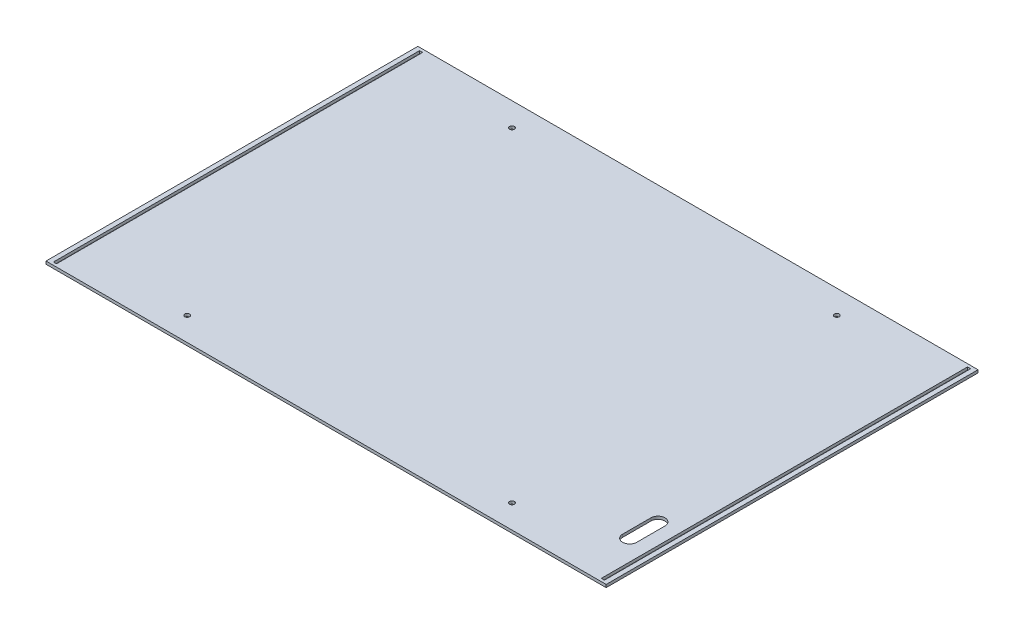
SolidWorks part; units mm, degrees
ref_plane "Front Plane" through (0, 0, 0) normal (0, 0, 1) x (1, 0, 0)
ref_plane "Top Plane" through (0, 0, 0) normal (0, 1, 0) x (1, 0, 0)
ref_plane "Right Plane" through (0, 0, 0) normal (1, 0, 0) x (0, 0, -1)
sketch "Sketch1" plane through (0, 0, 0) normal (0, 1, 0) x (1, 0, 0)
  line L1 (-297.5, 197.5) -> (297.5, 197.5)
  line L2 (-297.5, 197.5) -> (-297.5, -197.5)
  line L3 (-297.5, -197.5) -> (297.5, -197.5)
  line L4 (297.5, 197.5) -> (297.5, -197.5)
  line L5 (-297.5, 197.5) -> (297.5, -197.5) construction
  line L6 (-297.5, -197.5) -> (297.5, 197.5) construction
  point P0 (0, 0)
  dimension "D1" = 595
  dimension "D2" = 395
extrude "Boss-Extrude1" add sketch "Sketch1" along normal blind 3
sketch "Sketch2" plane through (0, 3, 0) normal (0, 1, 0) x (1, 0, 0)
  line L3 (267.5, -112.5) -> (267.5, -142.5) construction
  line L4 (275, -112.5) -> (275, -142.5)
  line L5 (260, -112.5) -> (260, -142.5)
  line L11 (-297.5, -197.5) -> (297.5, -197.5) construction
  arc A2 (275, -112.5) -> (260, -112.5) centre (267.5, -112.5) ccw
  arc A3 (260, -142.5) -> (275, -142.5) centre (267.5, -142.5) ccw
  point P7 (267.5, -127.5)
  dimension "D5" = 70
  dimension "D6" = 30
  dimension "D7" = 15
extrude "Cut-Extrude1" cut sketch "Sketch2" against normal blind 10
sketch "Sketch5" plane through (0, 3, 0) normal (0, 1, 0) x (1, 0, 0)
  line L0 (-289.5, 194.5) -> (-289.5, -194.5) construction
  line L1 (-289.35, 194.5) -> (-292.65, 194.5)
  line L2 (-289.35, 194.5) -> (-289.35, -194.5)
  line L3 (-289.35, -194.5) -> (-292.65, -194.5)
  line L4 (-292.65, 194.5) -> (-292.65, -194.5)
  line L5 (-289.35, 194.5) -> (-292.65, -194.5) construction
  line L6 (-289.35, -194.5) -> (-292.65, 194.5) construction
  line L8 (289.35, -194.5) -> (292.65, -194.5)
  line L9 (289.35, -194.5) -> (289.35, 194.5)
  line L10 (289.35, 194.5) -> (292.65, 194.5)
  line L11 (292.65, -194.5) -> (292.65, 194.5)
  line L12 (289.35, -194.5) -> (292.65, 194.5) construction
  line L13 (289.35, 194.5) -> (292.65, -194.5) construction
  line L14 (297.5, -197.5) -> (297.5, 197.5) construction
  point P0 (-291, 0)
  point P7 (291, 0)
  dimension "D1" = 1.5
  dimension "D2" = 389
  dimension "D3" = 3.3
  dimension "D4" = 3.3
  dimension "D5" = 389
  dimension "D6" = 4.85
extrude "Cut-Extrude2" cut sketch "Sketch5" against normal through all both and the other way through all
sketch "Sketch6" plane through (0, 3, 0) normal (0, 1, 0) x (1, 0, 0)
  circle A0 centre (172.5, 172.5) radius 2.6
  circle A1 centre (-172.5, -172.5) radius 2.6
  circle A2 centre (172.5, -172.5) radius 2.6
  circle A3 centre (-172.5, 172.5) radius 2.6
extrude "Cut-Extrude3" cut sketch "Sketch6" against normal through all both and the other way through all
